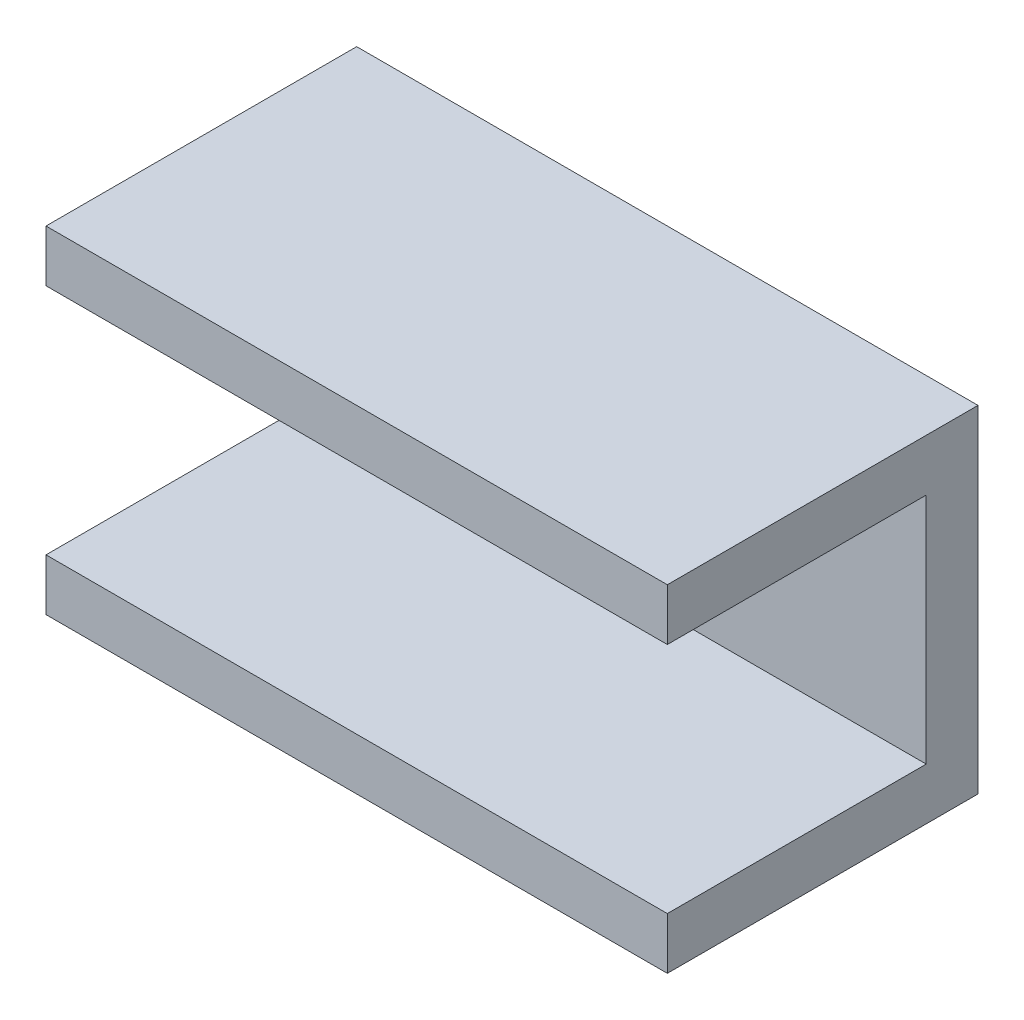
SolidWorks part; units mm, degrees
material "Custom Plastic"
ref_plane "X-Y Datum" through (0, 0, 0) normal (0, 0, 1) x (1, 0, 0)
ref_plane "X-Z Datum" through (0, 0, 0) normal (0, 1, 0) x (1, 0, 0)
ref_plane "Y-Z Datum" through (0, 0, 0) normal (1, 0, 0) x (0, 0, -1)
sketch "Sketch4" plane through (0, 0, 0) normal (1, 0, 0) x (0, 0, -1)
  line L0 (0, 20.6375) -> (0, -20.6375)
  line L1 (0, 20.6375) -> (-38.1, 20.6375)
  line L2 (-38.1, 20.6375) -> (-38.1, 14.2875)
  line L3 (-38.1, 14.2875) -> (-6.35, 14.2875)
  line L4 (-6.35, 14.2875) -> (-6.35, -14.2875)
  line L5 (-6.35, 0) -> (0, 0)
  line L6 (0, -20.6375) -> (-38.1, -20.6375)
  line L7 (-38.1, -20.6375) -> (-38.1, -14.2875)
  line L8 (-38.1, -14.2875) -> (-6.35, -14.2875)
  point P1 (0, 0)
  point P4 (0, 0)
  dimension "D1" = 6.35
  dimension "D2" = 14.2875
  dimension "D3" = 6.35
  dimension "D4" = 38.1
extrude "Boss-Extrude2" add sketch "Sketch4" along normal blind 76.2 contours L4 L5 L0 L1 L2 L3 | L8 L7 L6 L0 L5 L4
sketch "Sketch2" plane through (0, 20.6375, 0) normal (0, 1, 0) x (1, 0, 0)
  line L0 (54.5319, -38.1) -> (12.7, -38.1)
  line L1 (38.3233, -33.4461) -> (39.6981, -32.6523) construction
  line L2 (12.7, -18.9103) -> (127, -216.8837) construction
  line L3 (25.4, -40.9073) -> (11.1019, -49.1623) construction
  line L4 (12.7, -18.9103) -> (12.7, -161.3048) construction
  line L5 (11.1019, -49.1623) -> (112.7019, -225.1387) construction
  line L6 (112.7019, -225.1387) -> (127, -216.8837) construction
  line L7 (25.4, -40.9073) -> (38.3233, -33.4461) construction
  line L11 (0, 0) -> (63.5, 0)
  line L13 (0, 0) -> (0, -6.35)
  line L15 (30.4356, -37.465) -> (30.4356, -30.6832) construction
  line L16 (30.4356, -37.465) -> (20.5296, -37.465) construction
  line L18 (30.4356, -9.525) -> (20.5296, -9.525) construction
  line L20 (30.4356, -30.6832) -> (35.5156, -30.6832) construction
  line L21 (35.5156, -30.6832) -> (35.5156, -16.3068) construction
  line L22 (35.5156, -16.3068) -> (30.4356, -16.3068) construction
  line L23 (30.4356, -16.3068) -> (30.4356, -9.525) construction
  line L24 (20.5296, -37.465) -> (20.5296, -9.525) construction
  line L25 (54.5319, -38.1) -> (63.5, 0)
  line L26 (0, 0) -> (0, -38.1) construction
  line L27 (0, -6.35) -> (12.7, -38.1)
  line L28 (76.2, -38.1) -> (0, -38.1) construction
  circle A0 centre (12.7, -18.9103) radius 3.9688
  circle A1 centre (38.3233, -33.4461) radius 1.5875
  point P2 (4.0942, -34.7138)
  point P8 (8.5791, -38.1)
  point P9 (25.4, -40.9073)
  point P17 (12.7, -38.1)
  point P30 (35.5156, -23.495)
  point P31 (20.5296, -23.495)
  dimension "D1" = 7.9375
  dimension "D8" = 3.175
  dimension "D10" = 3.175
  dimension "D11" = 6.35
  dimension "D16" = 27.94
  dimension "D3" = 12.5603
  dimension "D4" = 16.51
  dimension "D5" = 228.6
  dimension "D6" = 25.4
  dimension "D7" = 30
  dimension "D9" = 16.51
  dimension "D19" = 14.986
  dimension "D21" = 5.08
  dimension "D22" = 14.3764
